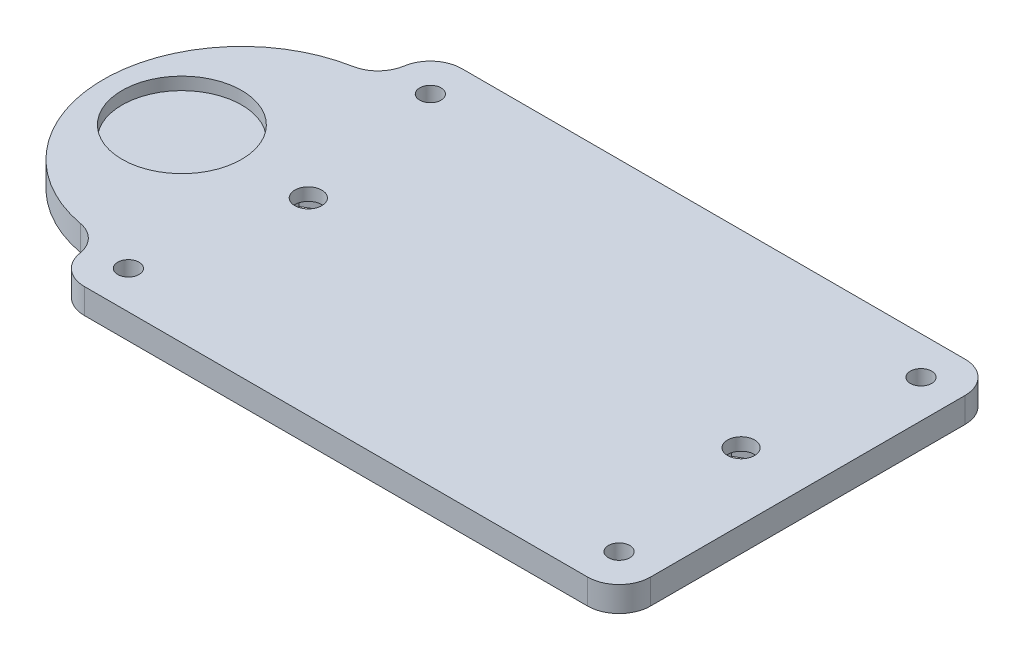
SolidWorks part; units mm, degrees
ref_plane "Front Plane" through (0, 0, 0) normal (0, 0, 1) x (1, 0, 0)
ref_plane "Top Plane" through (0, 0, 0) normal (0, 1, 0) x (1, 0, 0)
ref_plane "Right Plane" through (0, 0, 0) normal (1, 0, 0) x (0, 0, -1)
sketch "Sketch1" plane through (0, 0, 0) normal (0, 1, 0) x (1, 0, 0)
  line L1 (-45, 30) -> (45, 30)
  line L2 (-45, 30) -> (-45, -30)
  line L3 (-45, -30) -> (45, -30)
  line L4 (45, 30) -> (45, -30)
  dimension "D1" = 90
  dimension "D2" = 45
  dimension "D3" = 60
  dimension "D4" = 30
extrude "Boss-Extrude1" add sketch "Sketch1" along normal blind 4
sketch "Sketch2" plane through (0, 4, 0) normal (0, 1, 0) x (1, 0, 0)
  line L0 (45, 30) -> (-45, 30) construction
  line L1 (-45, 30) -> (-45, -30) construction
  line L2 (-45, -30) -> (45, -30) construction
  line L3 (45, -30) -> (45, 30) construction
  circle A0 centre (-39, 24) radius 1.7
  circle A1 centre (-39, -24) radius 1.7
  circle A2 centre (39, -24) radius 1.7
  circle A3 centre (39, 24) radius 1.7
  circle A5 centre (-34.4, 0) radius 2.15
  circle A6 centre (34.4, 0) radius 2.15
  dimension "D1" = 3.4
  dimension "D10" = 4.3
  dimension "D2" = 6
  dimension "D3" = 6
  dimension "D4" = 6
  dimension "D5" = 6
  dimension "D6" = 6
  dimension "D7" = 6
  dimension "D8" = 6
  dimension "D9" = 6
  dimension "D11" = 68.8
  dimension "D12" = 34.4
  dimension "D13" = 30
  dimension "D14" = 30
extrude "Cut-Extrude1" cut sketch "Sketch2" against normal blind 4
sketch "Sketch3" plane through (0, 0, 0) normal (0, -1, 0) x (1, 0, 0)
  line L0 (45, 30) -> (45, -30) construction
  line L1 (-30.825, 2.064) -> (-34.4, 4.1281)
  line L2 (-34.4, 4.1281) -> (-37.975, 2.064)
  line L3 (-37.975, 2.064) -> (-37.975, -2.064)
  line L4 (-37.975, -2.064) -> (-34.4, -4.1281)
  line L5 (-34.4, -4.1281) -> (-30.825, -2.064)
  line L6 (-30.825, -2.064) -> (-30.825, 2.064)
  line L7 (37.975, 2.064) -> (34.4, 4.1281)
  line L8 (34.4, 4.1281) -> (30.825, 2.064)
  line L9 (30.825, 2.064) -> (30.825, -2.064)
  line L10 (30.825, -2.064) -> (34.4, -4.1281)
  line L11 (34.4, -4.1281) -> (37.975, -2.064)
  line L12 (37.975, -2.064) -> (37.975, 2.064)
  line L13 (-45, -30) -> (-45, 30) construction
  circle A0 centre (-34.4, 0) radius 3.575 construction
  circle A1 centre (34.4, 0) radius 3.575 construction
  point P22 (-30.825, 0)
  dimension "D1" = 7.15
  dimension "D2" = 7.15
extrude "Cut-Extrude2" cut sketch "Sketch3" against normal blind 2
sketch "Sketch4" plane through (0, 4, 0) normal (0, 1, 0) x (1, 0, 0)
  line L1 (-45, 30) -> (-45, -30) construction
  line L2 (-45, 22) -> (-45, -22)
  arc A1 (-45, 22) -> (-45, -22) centre (-45, 0) ccw
  dimension "D1" = 22
extrude "Boss-Extrude2" add sketch "Sketch4" against normal blind 4
sketch "Sketch5" plane through (0, 4, 0) normal (0, 1, 0) x (1, 0, 0)
  circle A0 centre (-54.5, 0) radius 9.5
  point P3 (0, 0)
  dimension "D1" = 19
extrude "Cut-Extrude3" cut sketch "Sketch5" against normal blind 2
fillet "Fillet3" radius 5 4 edges at (45, 2, -30) (-45, 2, -30) (45, 2, 30) (-45, 2, 30)
fillet "Fillet4" radius 5 2 edges at (-45, 2, -22) (-45, 2, 22)
